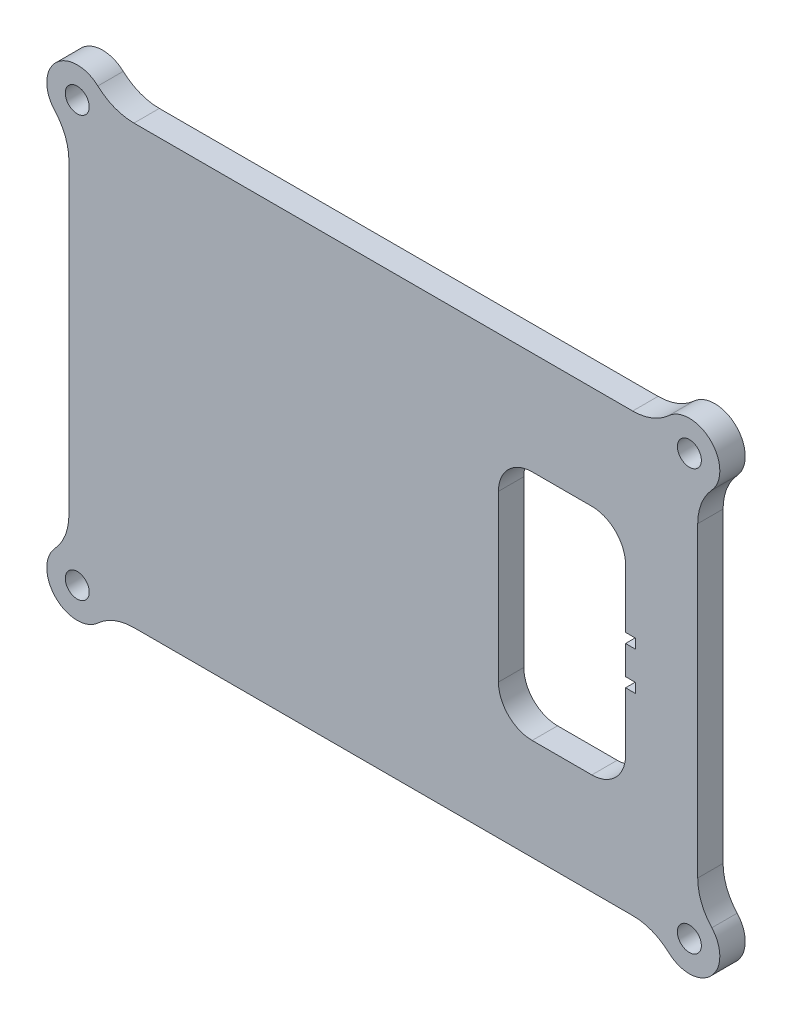
SolidWorks part; units mm, degrees
material "Acrylic (Medium-high impact)"
ref_plane "X-Y Datum" through (0, 0, 0) normal (0, 0, 1) x (1, 0, 0)
ref_plane "X-Z Datum" through (0, 0, 0) normal (0, 1, 0) x (1, 0, 0)
ref_plane "Y-Z Datum" through (0, 0, 0) normal (1, 0, 0) x (0, 0, -1)
sketch "Sketch2" plane through (0, 0, 0) normal (0, 0, 1) x (1, 0, 0)
  line L0 (-68.0552, 8.0026) -> (-68.0552, -49.5872) construction
  line L1 (-55.85, -61.7923) -> (37.7397, -61.7923) construction
  line L2 (49.9448, -49.5872) -> (49.9448, 8.0026) construction
  line L3 (37.7397, 20.2077) -> (-55.85, 20.2077) construction
  line L4 (-68.0552, 8.0026) -> (-68.0552, -49.5872)
  line L5 (-55.85, -61.7923) -> (37.7397, -61.7923)
  line L6 (49.9448, -49.5872) -> (49.9448, 8.0026)
  line L7 (37.7397, 20.2077) -> (-55.85, 20.2077)
  line L10 (18.8768, -42.6373) -> (30.0768, -42.6373) construction
  line L11 (36.2768, -36.4373) -> (36.2768, -25.4373) construction
  line L12 (36.2768, -23.6373) -> (36.2768, -25.4373) construction
  line L13 (36.2768, -16.4373) -> (36.2768, -18.2373) construction
  line L14 (36.2768, -18.2373) -> (36.2768, -23.6373) construction
  line L15 (36.2768, -16.4373) -> (36.2768, -5.4373) construction
  line L24 (12.6768, -5.4373) -> (12.6768, -36.4373) construction
  line L33 (30.0768, 0.7627) -> (18.8768, 0.7627) construction
  line L36 (18.8768, -42.6373) -> (30.0768, -42.6373) construction
  line L37 (36.2768, -36.4373) -> (36.2768, -25.4373) construction
  line L38 (36.2768, -23.6373) -> (36.2768, -25.4373) construction
  line L39 (36.2768, -16.4373) -> (36.2768, -18.2373) construction
  line L40 (36.2768, -18.2373) -> (36.2768, -23.6373) construction
  line L41 (36.2768, -16.4373) -> (36.2768, -5.4373) construction
  line L54 (12.6768, -5.4373) -> (12.6768, -36.4373) construction
  line L55 (30.0768, 0.7627) -> (18.8768, 0.7627) construction
  line L56 (30.0768, 0.8877) -> (18.8768, 0.8877)
  line L57 (12.5518, -5.4373) -> (12.5518, -36.4373)
  line L58 (18.8768, -42.7623) -> (30.0768, -42.7623)
  line L59 (36.4018, -36.4373) -> (36.4018, -25.4373)
  line L61 (36.4018, -18.2373) -> (36.4018, -23.6373)
  line L63 (36.4018, -16.4373) -> (36.4018, -5.4373)
  line L64 (36.4018, -16.4373) -> (38.2768, -16.4373)
  line L65 (38.2768, -16.4373) -> (38.2768, -18.2373)
  line L66 (38.2768, -18.2373) -> (36.4018, -18.2373)
  line L67 (36.4018, -23.6373) -> (38.2768, -23.6373)
  line L68 (38.2768, -23.6373) -> (38.2768, -25.4373)
  line L69 (36.4018, -23.6373) -> (36.4018, -25.4373) construction
  line L70 (36.4018, -16.4373) -> (36.4018, -18.2373) construction
  line L71 (38.2768, -25.4373) -> (36.4018, -25.4373)
  arc A0 (-70.696, -56.3579) -> (-68.0552, -49.5872) centre (-78.0552, -49.5872) ccw construction
  arc A1 (-70.696, -56.3579) -> (-62.6207, -64.4331) centre (-66.4902, -60.2273) ccw construction
  arc A2 (-55.85, -61.7923) -> (-62.6207, -64.4331) centre (-55.85, -71.7923) ccw construction
  arc A3 (44.5104, -64.4331) -> (37.7397, -61.7923) centre (37.7397, -71.7923) ccw construction
  arc A4 (44.5104, -64.4331) -> (52.5857, -56.3579) centre (48.3799, -60.2273) ccw construction
  arc A5 (49.9448, -49.5872) -> (52.5857, -56.3579) centre (59.9448, -49.5872) ccw construction
  arc A6 (52.5857, 14.7733) -> (49.9448, 8.0026) centre (59.9448, 8.0026) ccw construction
  arc A7 (52.5857, 14.7733) -> (44.5104, 22.8485) centre (48.3799, 18.6427) ccw construction
  arc A8 (37.7397, 20.2077) -> (44.5104, 22.8485) centre (37.7397, 30.2077) ccw construction
  arc A9 (-62.6207, 22.8485) -> (-55.85, 20.2077) centre (-55.85, 30.2077) ccw construction
  arc A50 (-62.6207, 22.8485) -> (-70.696, 14.7733) centre (-66.4902, 18.6427) ccw construction
  arc A51 (-68.0552, 8.0026) -> (-70.696, 14.7733) centre (-78.0552, 8.0026) ccw construction
  circle A52 centre (-66.4902, 18.6427) radius 2.25
  circle A53 centre (48.3799, 18.6427) radius 2.25
  circle A54 centre (48.3799, -60.2273) radius 2.25
  circle A55 centre (-66.4902, -60.2273) radius 2.25
  arc A59 (12.6768, -36.4373) -> (18.8768, -42.6373) centre (18.8768, -36.4373) ccw construction
  arc A60 (30.0768, -42.6373) -> (36.2768, -36.4373) centre (30.0768, -36.4373) ccw construction
  arc A61 (18.8768, 0.7627) -> (12.6768, -5.4373) centre (18.8768, -5.4373) ccw construction
  arc A62 (36.2768, -5.4373) -> (30.0768, 0.7627) centre (30.0768, -5.4373) ccw construction
  arc A63 (12.6768, -36.4373) -> (18.8768, -42.6373) centre (18.8768, -36.4373) ccw construction
  arc A76 (-70.696, -56.3579) -> (-68.0552, -49.5872) centre (-78.0552, -49.5872) ccw
  arc A77 (-70.696, -56.3579) -> (-62.6207, -64.4331) centre (-66.4902, -60.2273) ccw
  arc A78 (-55.85, -61.7923) -> (-62.6207, -64.4331) centre (-55.85, -71.7923) ccw
  arc A79 (44.5104, -64.4331) -> (37.7397, -61.7923) centre (37.7397, -71.7923) ccw
  arc A80 (44.5104, -64.4331) -> (52.5857, -56.3579) centre (48.3799, -60.2273) ccw
  arc A81 (49.9448, -49.5872) -> (52.5857, -56.3579) centre (59.9448, -49.5872) ccw
  arc A82 (52.5857, 14.7733) -> (49.9448, 8.0026) centre (59.9448, 8.0026) ccw
  arc A83 (52.5857, 14.7733) -> (44.5104, 22.8485) centre (48.3799, 18.6427) ccw
  arc A84 (37.7397, 20.2077) -> (44.5104, 22.8485) centre (37.7397, 30.2077) ccw
  arc A85 (-62.6207, 22.8485) -> (-55.85, 20.2077) centre (-55.85, 30.2077) ccw
  arc A86 (-62.6207, 22.8485) -> (-70.696, 14.7733) centre (-66.4902, 18.6427) ccw
  arc A87 (-68.0552, 8.0026) -> (-70.696, 14.7733) centre (-78.0552, 8.0026) ccw
  arc A88 (30.0768, -42.6373) -> (36.2768, -36.4373) centre (30.0768, -36.4373) ccw construction
  arc A89 (18.8768, 0.7627) -> (12.6768, -5.4373) centre (18.8768, -5.4373) ccw construction
  arc A90 (36.2768, -5.4373) -> (30.0768, 0.7627) centre (30.0768, -5.4373) ccw construction
  arc A91 (18.8768, 0.8877) -> (12.5518, -5.4373) centre (18.8768, -5.4373) ccw
  arc A92 (12.5518, -36.4373) -> (18.8768, -42.7623) centre (18.8768, -36.4373) ccw
  arc A93 (30.0768, -42.7623) -> (36.4018, -36.4373) centre (30.0768, -36.4373) ccw
  arc A94 (36.4018, -5.4373) -> (30.0768, 0.8877) centre (30.0768, -5.4373) ccw
  point P1 (-66.4902, 18.6427)
  point P4 (48.3799, 18.6427)
  point P6 (48.3799, -60.2273)
  point P7 (-66.4902, -60.2273)
  dimension "D1" = 4.5
  dimension "D2" = 0.125
extrude "Boss-Extrude1" add sketch "Sketch2" along normal blind 4.7625
